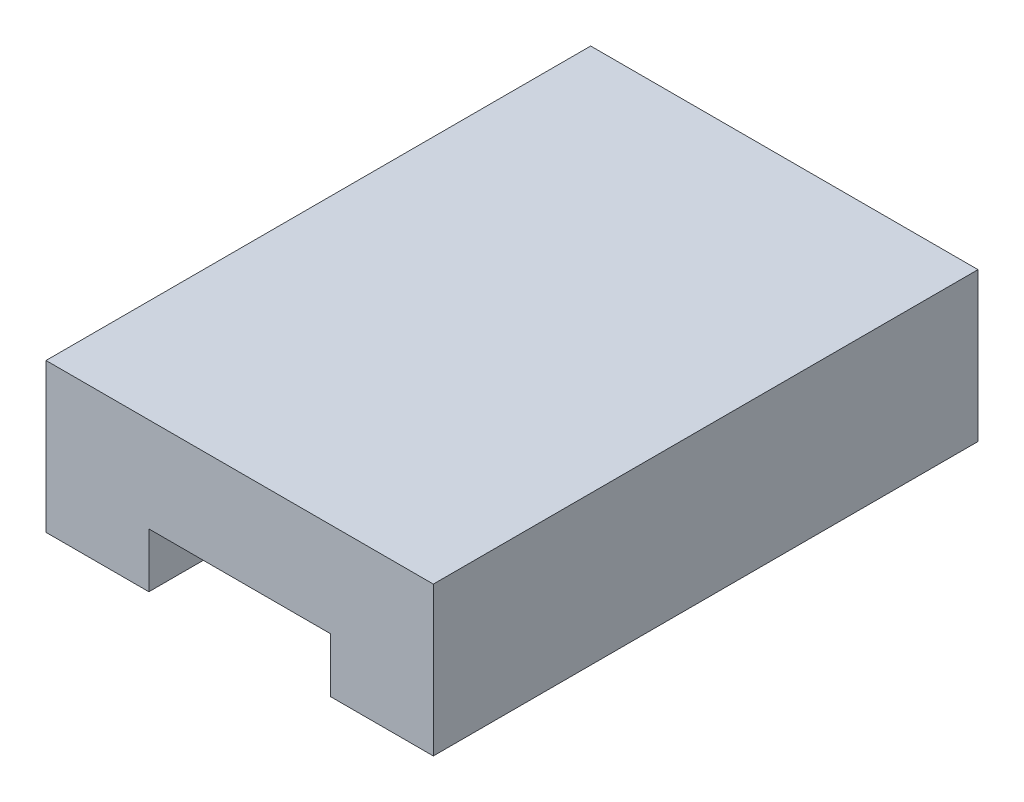
SolidWorks part; units mm, degrees
ref_plane "前视基准面" through (0, 0, 0) normal (0, 0, 1) x (1, 0, 0)
ref_plane "上视基准面" through (0, 0, 0) normal (0, 1, 0) x (1, 0, 0)
ref_plane "右视基准面" through (0, 0, 0) normal (1, 0, 0) x (0, 0, -1)
sketch "草图1" plane through (0, 0, 0) normal (0, 0, 1) x (1, 0, 0)
  line L0 (0, 6.15) -> (32, 6.15) construction
  line L1 (0, 0) -> (32, 0)
  line L2 (0, 0) -> (0, 12.3)
  line L3 (0, 12.3) -> (32, 12.3)
  line L4 (32, 0) -> (32, 12.3)
  line L5 (16, 12.3) -> (16, 0) construction
  line L6 (8.5, 0) -> (23.5, 0)
  line L7 (8.5, 0) -> (8.5, 4.5)
  line L8 (8.5, 4.5) -> (23.5, 4.5)
  line L9 (23.5, 4.5) -> (23.5, 0)
  point P11 (16, 0)
  dimension "D1" = 32
  dimension "D2" = 12.3
  dimension "D3" = 15
  dimension "D4" = 4.5
extrude "凸台-拉伸2" add sketch "草图1" along normal blind 45 contours L8 L9 L1 L4 L3 L2 L7
